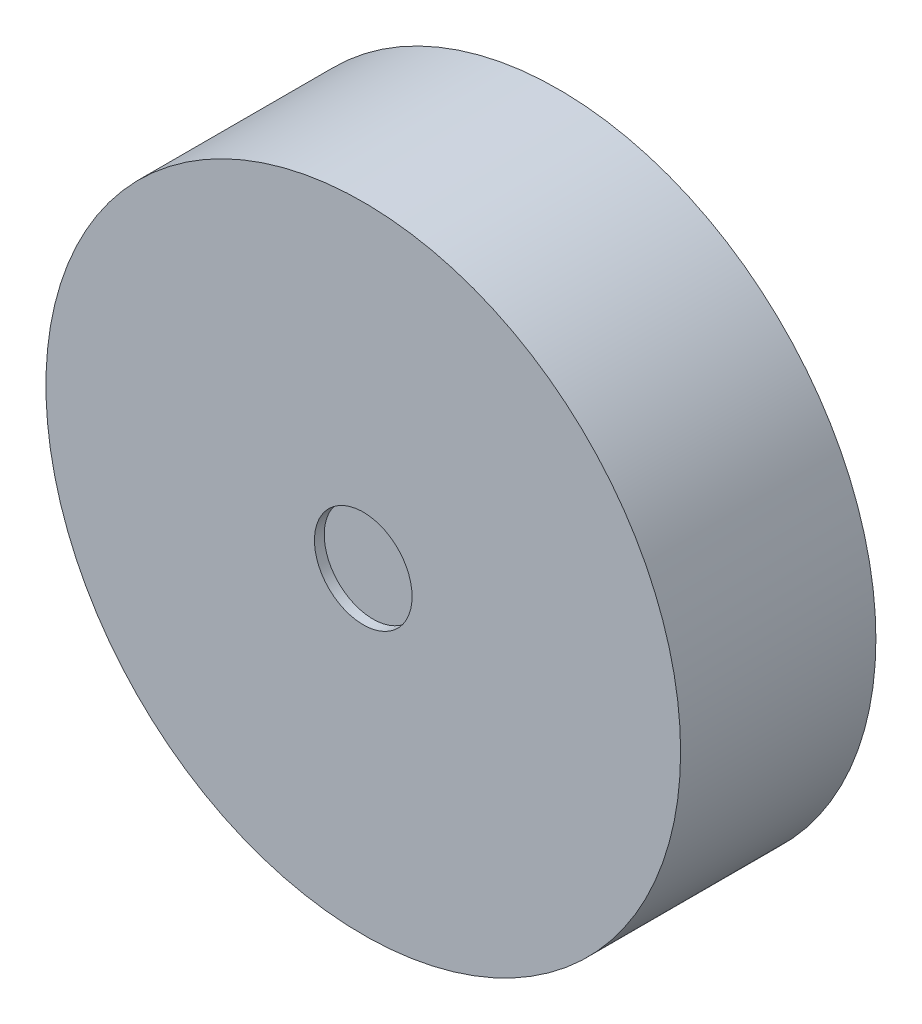
SolidWorks part; units mm, degrees
ref_plane "Front Plane" through (0, 0, 0) normal (0, 0, 1) x (1, 0, 0)
ref_plane "Top Plane" through (0, 0, 0) normal (0, 1, 0) x (1, 0, 0)
ref_plane "Right Plane" through (0, 0, 0) normal (1, 0, 0) x (0, 0, -1)
sketch "Sketch1" plane through (0, 0, 0) normal (0, 0, 1) x (1, 0, 0)
  circle A0 centre (0, 0) radius 32.5
  dimension "D1" = 65
extrude "Boss-Extrude1" add sketch "Sketch1" along normal blind 20
sketch "Sketch2" plane through (0, 0, 20) normal (0, 0, 1) x (1, 0, 0)
  circle A0 centre (0, 0) radius 5
  dimension "D1" = 10
extrude "Cut-Extrude1" cut sketch "Sketch2" against normal blind 1
sketch "Sketch3" plane through (0, 0, 0) normal (0, 0, -1) x (-1, 0, 0)
  line L0 (11, 0) -> (-11, 0) construction
  line L1 (-5.5, -9) -> (5.5, -9) construction
  line L2 (-5.5, -9) -> (-5.5, 9) construction
  line L3 (-5.5, 9) -> (5.5, 9) construction
  line L4 (5.5, -9) -> (5.5, 9) construction
  line L5 (-5.5, -9) -> (5.5, 9) construction
  line L6 (-5.5, 9) -> (5.5, -9) construction
  line L7 (-7.5, 11) -> (20.5, 11) construction
  line L8 (-7.5, 11) -> (-7.5, -11) construction
  line L9 (-7.5, -11) -> (20.5, -11) construction
  line L10 (20.5, 11) -> (20.5, -11) construction
  circle A0 centre (5.5, 9) radius 1.5
  circle A1 centre (-5.5, 9) radius 1.5
  circle A2 centre (5.5, -9) radius 1.5
  circle A3 centre (-5.5, -9) radius 1.5
  circle A5 centre (-5.5, 9) radius 3 construction
  circle A6 centre (5.5, 9) radius 3 construction
  circle A7 centre (5.5, -9) radius 3 construction
  circle A8 centre (-5.5, -9) radius 3 construction
  point P0 (0, 0)
  point P14 (20.5, 0)
  dimension "D1" = 3
  dimension "D7" = 1.5
  dimension "D2" = 11
  dimension "D3" = 18
  dimension "D4" = 22
  dimension "D5" = 28
  dimension "D6" = 2
sketch "Sketch4" plane through (0, 0, 0) normal (0, 0, -1) x (-1, 0, 0)
  circle A0 centre (0, 0) radius 3.05
  dimension "D1" = 6.1
extrude "Cut-Extrude2" cut sketch "Sketch4" against normal blind 4.5
extrude "Cut-Extrude3" cut sketch "Sketch3" against normal blind 2
sketch "Sketch5" plane through (0, 0, 0) normal (0, 0, -1) x (-1, 0, 0)
  circle A0 centre (0, 0) radius 5
  dimension "D1" = 10
extrude "Cut-Extrude4" cut sketch "Sketch5" against normal blind 2
